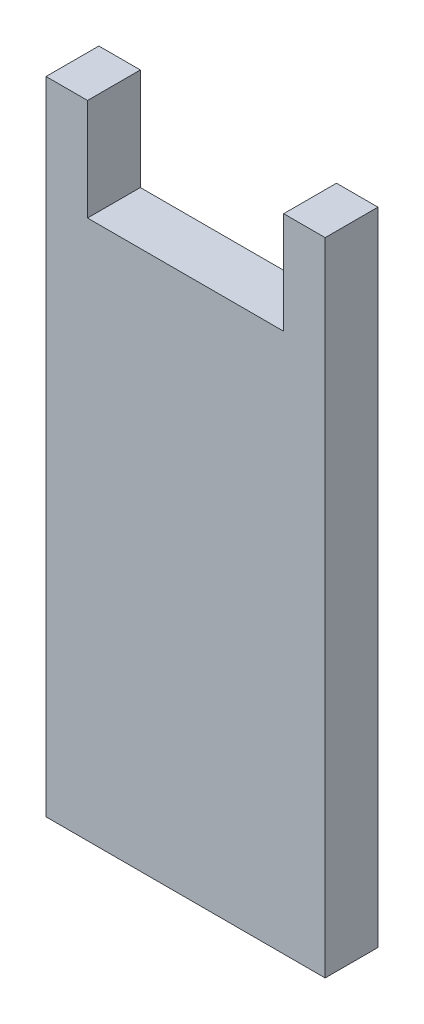
SolidWorks part; units mm, degrees
ref_plane "Front Plane" through (0, 0, 0) normal (0, 0, 1) x (1, 0, 0)
ref_plane "Top Plane" through (0, 0, 0) normal (0, 1, 0) x (1, 0, 0)
ref_plane "Right Plane" through (0, 0, 0) normal (1, 0, 0) x (0, 0, -1)
sketch "Sketch1" plane through (0, 0, 0) normal (0, 0, 1) x (1, 0, 0)
  line L0 (14.5, 67.2609) -> (14.5, 80.7609)
  line L3 (-17, -4.2391) -> (20, -4.2391)
  line L5 (14.5, 80.7609) -> (20, 80.7609)
  line L8 (-17, 80.7609) -> (-11.5, 80.7609)
  line L9 (-11.5, 80.7609) -> (-11.5, 67.2609)
  line L10 (-11.5, 67.2609) -> (14.5, 67.2609)
  line L11 (20, 80.7609) -> (20, -4.2391)
  line L12 (-17, -4.2391) -> (-17, 80.7609)
  point P0 (0, 0)
  dimension "D1" = 13.5
  dimension "D2" = 85
  dimension "D3" = 26
  dimension "D4" = 5.5
  dimension "D5" = 5.5
extrude "Boss-Extrude1" add sketch "Sketch1" against normal blind 7
